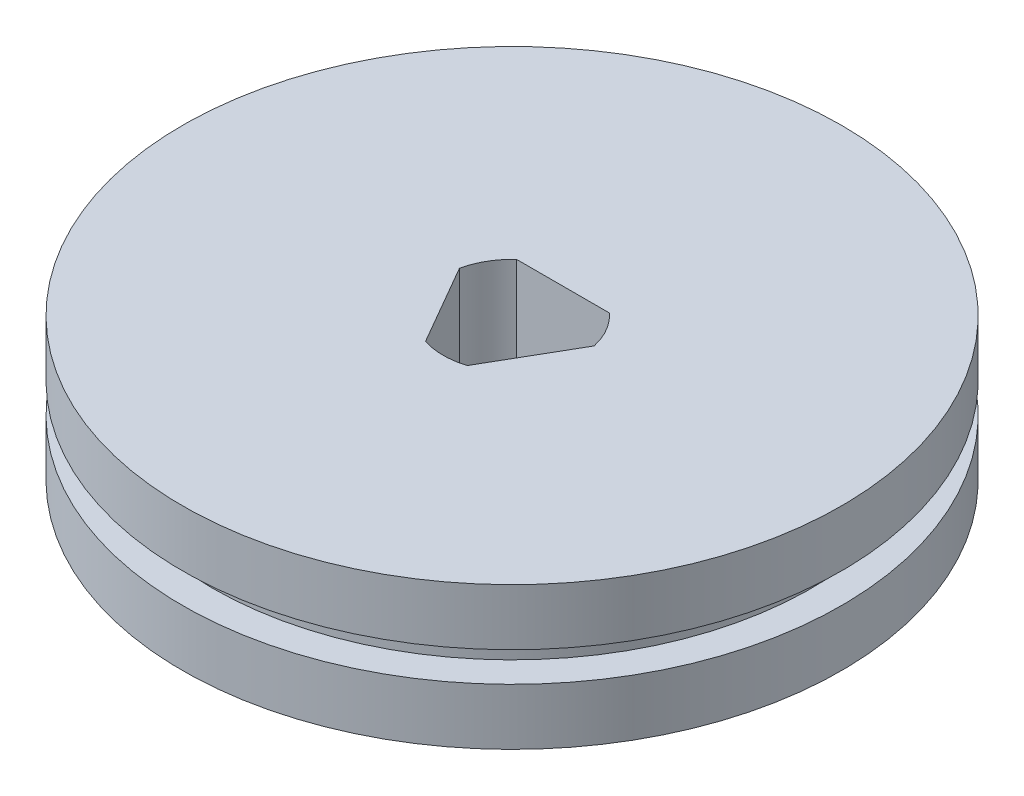
SolidWorks part; units mm, degrees
material "ABS"
ref_plane "Plano frontal" through (0, 0, 0) normal (0, 0, 1) x (1, 0, 0)
ref_plane "Plano superior" through (0, 0, 0) normal (0, 1, 0) x (1, 0, 0)
ref_plane "Plano direito" through (0, 0, 0) normal (1, 0, 0) x (0, 0, -1)
sketch "Esboço1" plane through (0, 0, 0) normal (0, 1, 0) x (1, 0, 0)
  circle A0 centre (0, 0) radius 11
  dimension "D1" = 22
extrude "Ressalto-extrusão1" add sketch "Esboço1" along normal mid plane 4.7625
sketch "Esboço2" plane through (0, 0, 0) normal (0, 1, 0) x (1, 0, 0)
  circle A0 centre (0, 0) radius 10
  circle A1 centre (0, 0) radius 11
  circle A2 centre (0, 0) radius 11 construction
  dimension "D1" = 20
extrude "Corte-extrusão1" cut sketch "Esboço2" against normal mid plane 1
sketch "Esboço4" plane through (0, 2.3813, 0) normal (0, 1, 0) x (1, 0, 0)
  line L0 (-2.2468, 0.4916) -> (-0.6976, -2.1916)
  line L1 (0.6976, -2.1916) -> (2.2468, 0.4916)
  line L2 (1.5492, 1.7) -> (-1.5492, 1.7)
  line L3 (-1.4722, -0.85) -> (1.9919, 1.15) construction
  line L4 (0, 1.7) -> (0, -2.3) construction
  arc A0 (-1.5492, 1.7) -> (-2.2468, 0.4916) centre (0, 0) ccw
  arc A1 (-0.6976, -2.1916) -> (0.6976, -2.1916) centre (0, 0) ccw
  arc A2 (1.5492, 1.7) -> (2.2468, 0.4916) centre (0, 0) cw
  dimension "D1" = 2.3
  dimension "D2" = 4
extrude "Corte-extrusão3" cut sketch "Esboço4" against normal through all
